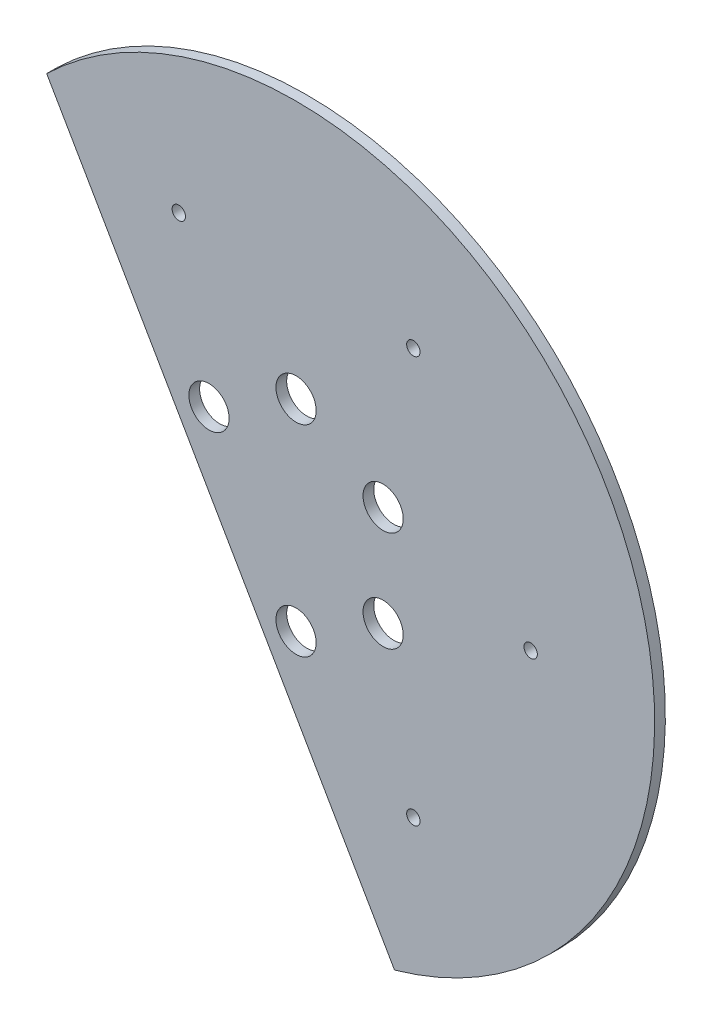
SolidWorks part; units mm, degrees
ref_plane "Plan de face" through (0, 0, 0) normal (0, 0, 1) x (1, 0, 0)
ref_plane "Plan de dessus" through (0, 0, 0) normal (0, 1, 0) x (1, 0, 0)
ref_plane "Plan de droite" through (0, 0, 0) normal (1, 0, 0) x (0, 0, -1)
sketch "Esquisse1" plane through (0, 0, 0) normal (0, 0, 1) x (1, 0, 0)
  circle A12 centre (0, 0) radius 53.5
  line B0 (0, 15) -> (0, -15) construction
  circle B1 centre (35, 0) radius 1
  circle B2 centre (17.5, -30.3109) radius 1
  circle B3 centre (-17.5, -30.3109) radius 1
  circle B4 centre (-35, 0) radius 1
  circle B5 centre (-17.5, 30.3109) radius 1
  circle B6 centre (17.5, 30.3109) radius 1
  circle B7 centre (0, -15) radius 3
  circle B8 centre (12.9904, -7.5) radius 3
  circle B9 centre (12.9904, 7.5) radius 3
  circle B10 centre (0, 15) radius 3
  circle B11 centre (-12.9904, 7.5) radius 3
  dimension "D1" = 107
sketch_block_instance "Bloc1-1"
sketch_block "Bloc1" parameters "D1"=2
extrude "Boss.-Extru.1" add sketch "Esquisse1" along normal blind 1.6
sketch "Esquisse2" plane through (0, 0, 1.6) normal (0, 0, 1) x (1, 0, 0)
  line L0 (-37.2066, 38.4437) -> (14.6899, -51.4437)
  line L1 (0, 0) -> (12.9904, 7.5) construction
  circle A0 centre (0, 0) radius 53.5 construction
  arc A1 (-37.2066, 38.4437) -> (14.6899, -51.4437) centre (0, 0) ccw
  dimension "D1" = 13
extrude "Enlèv. mat.-Extru.1" cut sketch "Esquisse2" against normal through all
